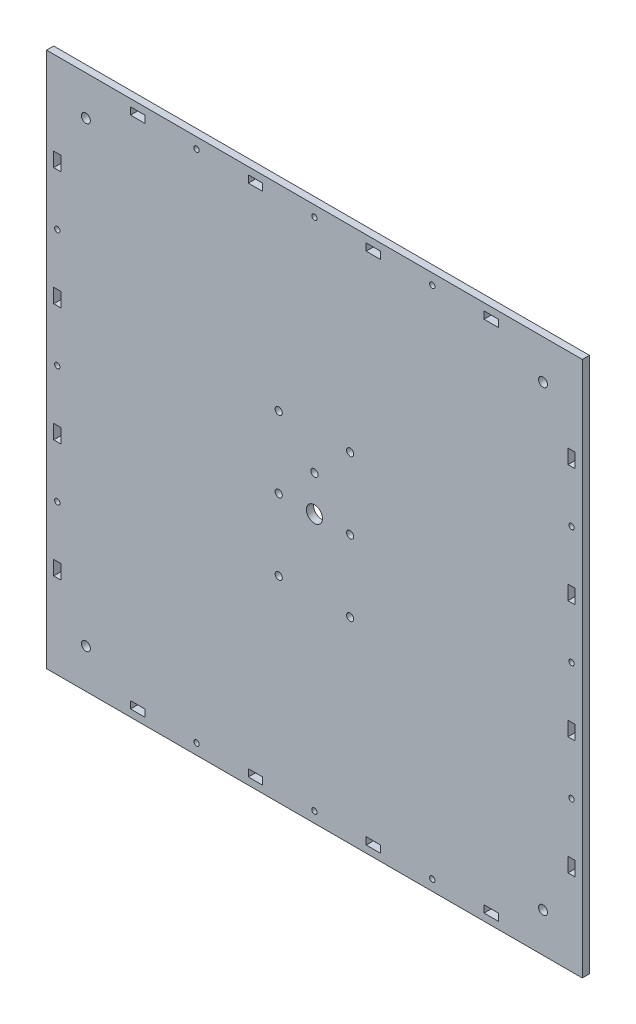
SolidWorks part; units mm, degrees
ref_plane "前视基准面" through (0, 0, 0) normal (0, 0, 1) x (1, 0, 0)
ref_plane "上视基准面" through (0, 0, 0) normal (0, 1, 0) x (1, 0, 0)
ref_plane "右视基准面" through (0, 0, 0) normal (1, 0, 0) x (0, 0, -1)
sketch "草图1" plane through (0, 0, 0) normal (0, 0, 1) x (1, 0, 0)
  line L0 (1.4571, -21.1871) -> (1.4571, -41.1871) construction
  line L1 (1.4571, -41.1871) -> (-18.5429, -41.1871) construction
  line L2 (1.4571, -21.1871) -> (1.4571, 44.8129) construction
  line L4 (151.4571, -41.1871) -> (151.4571, 108.8129)
  line L5 (151.4571, 108.8129) -> (-148.5429, 108.8129)
  line L6 (-148.5429, 108.8129) -> (-148.5429, -191.1871)
  line L7 (-148.5429, -191.1871) -> (151.4571, -191.1871)
  line L8 (151.4571, -191.1871) -> (151.4571, -41.1871)
  line L9 (-148.5429, -41.1871) -> (-161.9412, -41.1871) construction
  line L10 (1.4571, -191.1871) -> (1.4571, -181.0361) construction
  circle A0 centre (1.4571, -21.1871) radius 10 construction
  circle A1 centre (1.4571, -41.1871) radius 4.5
  circle A2 centre (-18.5429, -41.1871) radius 2
  circle A3 centre (-18.5429, -1.1871) radius 2
  circle A4 centre (21.4571, -1.1871) radius 2
  circle A5 centre (21.4571, -41.1871) radius 2
  circle A6 centre (1.4571, -21.1871) radius 241.4173 construction
  circle A7 centre (21.4571, -81.1871) radius 2
  circle A8 centre (-18.5429, -81.1871) radius 2
  dimension "D2" = 300
  dimension "D3" = 300
extrude "凸台-拉伸1" add sketch "草图1" along normal blind 4
sketch "草图2" plane through (0, 0, 4) normal (0, 0, 1) x (1, 0, 0)
  line L0 (-18.5429, -1.1871) -> (21.4571, -41.1871) construction
  circle A0 centre (1.4571, -21.1871) radius 2
extrude "切除-拉伸1" cut sketch "草图2" against normal blind 4 contours A0
sketch "草图3" plane through (0, 0, 4) normal (0, 0, 1) x (1, 0, 0)
  line L1 (96.4421, -183.1721) -> (104.4721, -183.1721)
  line L13 (1.4571, -191.1871) -> (1.4571, -185.1871) construction
  line L14 (-148.5429, -191.1871) -> (151.4571, -191.1871) construction
  line L15 (1.4571, -185.1871) -> (34.4571, -185.1871) construction
  line L16 (34.4571, -185.1871) -> (67.4571, -185.1871) construction
  line L17 (30.4421, -183.1721) -> (38.4721, -183.1721)
  line L18 (30.4421, -183.1721) -> (30.4421, -187.2021)
  line L19 (30.4421, -187.2021) -> (38.4721, -187.2021)
  line L20 (38.4721, -183.1721) -> (38.4721, -187.2021)
  line L21 (30.4421, -183.1721) -> (38.4721, -187.2021) construction
  line L22 (30.4421, -187.2021) -> (38.4721, -183.1721) construction
  line L23 (67.4571, -185.1871) -> (100.4571, -185.1871) construction
  line L24 (96.4421, -183.1721) -> (96.4421, -187.2021)
  line L25 (96.4421, -187.2021) -> (104.4721, -187.2021)
  line L26 (96.4421, -187.2021) -> (104.4721, -183.1721) construction
  line L27 (104.4721, -187.2021) -> (104.4721, -183.1721)
  line L28 (-35.5579, -183.1721) -> (-35.5579, -187.2021)
  line L29 (-27.5279, -183.1721) -> (-35.5579, -183.1721)
  line L30 (-27.5279, -183.1721) -> (-27.5279, -187.2021)
  line L31 (-27.5279, -187.2021) -> (-35.5579, -187.2021)
  line L32 (-93.5279, -183.1721) -> (-93.5279, -187.2021)
  line L33 (-101.5579, -187.2021) -> (-101.5579, -183.1721)
  line L34 (-93.5279, -183.1721) -> (-101.5579, -183.1721)
  line L35 (-93.5279, -187.2021) -> (-101.5579, -187.2021)
  line L36 (-140.5279, 53.7979) -> (-140.5279, 61.8279)
  line L37 (-144.5579, 53.7979) -> (-144.5579, 61.8279)
  line L38 (-144.5579, 61.8279) -> (-140.5279, 61.8279)
  line L39 (-140.5279, 53.7979) -> (-144.5579, 53.7979)
  line L40 (-140.5279, -12.2021) -> (-140.5279, -4.1721)
  line L41 (-140.5279, -4.1721) -> (-144.5579, -4.1721)
  line L42 (-144.5579, -12.2021) -> (-144.5579, -4.1721)
  line L43 (-140.5279, -12.2021) -> (-144.5579, -12.2021)
  line L44 (-140.5279, -70.1721) -> (-144.5579, -70.1721)
  line L45 (-140.5279, -70.1721) -> (-140.5279, -78.2021)
  line L46 (-144.5579, -70.1721) -> (-144.5579, -78.2021)
  line L47 (-140.5279, -78.2021) -> (-144.5579, -78.2021)
  line L48 (-140.5279, -136.1721) -> (-140.5279, -144.2021)
  line L49 (-144.5579, -136.1721) -> (-144.5579, -144.2021)
  line L50 (-140.5279, -136.1721) -> (-144.5579, -136.1721)
  line L51 (-144.5579, -144.2021) -> (-140.5279, -144.2021)
  line L52 (96.4421, 100.7979) -> (104.4721, 100.7979)
  line L53 (96.4421, 104.8279) -> (104.4721, 104.8279)
  line L54 (104.4721, 104.8279) -> (104.4721, 100.7979)
  line L55 (96.4421, 100.7979) -> (96.4421, 104.8279)
  line L56 (30.4421, 100.7979) -> (38.4721, 100.7979)
  line L57 (38.4721, 100.7979) -> (38.4721, 104.8279)
  line L58 (30.4421, 104.8279) -> (38.4721, 104.8279)
  line L59 (30.4421, 100.7979) -> (30.4421, 104.8279)
  line L60 (-27.5279, 100.7979) -> (-27.5279, 104.8279)
  line L61 (-27.5279, 100.7979) -> (-35.5579, 100.7979)
  line L62 (-27.5279, 104.8279) -> (-35.5579, 104.8279)
  line L63 (-35.5579, 100.7979) -> (-35.5579, 104.8279)
  line L64 (-93.5279, 100.7979) -> (-101.5579, 100.7979)
  line L65 (-93.5279, 104.8279) -> (-101.5579, 104.8279)
  line L66 (-93.5279, 100.7979) -> (-93.5279, 104.8279)
  line L67 (-101.5579, 104.8279) -> (-101.5579, 100.7979)
  line L68 (143.4421, -136.1721) -> (143.4421, -144.2021)
  line L69 (147.4721, -136.1721) -> (147.4721, -144.2021)
  line L70 (147.4721, -144.2021) -> (143.4421, -144.2021)
  line L71 (143.4421, -136.1721) -> (147.4721, -136.1721)
  line L72 (143.4421, -70.1721) -> (143.4421, -78.2021)
  line L73 (143.4421, -78.2021) -> (147.4721, -78.2021)
  line L74 (147.4721, -70.1721) -> (147.4721, -78.2021)
  line L75 (143.4421, -70.1721) -> (147.4721, -70.1721)
  line L76 (143.4421, -12.2021) -> (147.4721, -12.2021)
  line L77 (143.4421, -12.2021) -> (143.4421, -4.1721)
  line L78 (147.4721, -12.2021) -> (147.4721, -4.1721)
  line L79 (143.4421, -4.1721) -> (147.4721, -4.1721)
  line L80 (143.4421, 53.7979) -> (143.4421, 61.8279)
  line L81 (147.4721, 53.7979) -> (147.4721, 61.8279)
  line L82 (143.4421, 53.7979) -> (147.4721, 53.7979)
  line L83 (147.4721, 61.8279) -> (143.4421, 61.8279)
  circle A0 centre (1.4571, -185.1871) radius 1.5
  circle A1 centre (67.4571, -185.1871) radius 1.5
  circle A2 centre (-64.5429, -185.1871) radius 1.5
  circle A3 centre (-142.5429, 24.8129) radius 1.5
  circle A4 centre (-142.5429, -41.1871) radius 1.5
  circle A5 centre (-142.5429, -107.1871) radius 1.5
  circle A6 centre (67.4571, 102.8129) radius 1.5
  circle A7 centre (1.4571, 102.8129) radius 1.5
  circle A8 centre (-64.5429, 102.8129) radius 1.5
  circle A9 centre (145.4571, -107.1871) radius 1.5
  circle A10 centre (145.4571, -41.1871) radius 1.5
  circle A11 centre (145.4571, 24.8129) radius 1.5
  dimension "D1" = 8.03
  dimension "D3" = 4
  dimension "D2" = 4.03
extrude "切除-拉伸2" cut sketch "草图3" against normal blind 4
sketch "草图4" plane through (0, 0, 4) normal (0, 0, 1) x (1, 0, 0)
  line L2 (1.4571, 102.8129) -> (-142.5429, 102.8129) construction
  line L3 (-142.5429, 102.8129) -> (-38.5429, -1.1871) construction
  line L4 (1.4571, -1.1871) -> (-38.5429, -1.1871) construction
  line L5 (1.4571, 102.8129) -> (1.4571, -1.1871) construction
  line L6 (-9.5429, 88.8129) -> (-9.5429, 12.8129)
  line L7 (-12.5429, 9.8129) -> (-32.7439, 9.8129)
  line L8 (-110.8652, 86.6915) -> (-34.8652, 10.6915)
  line L9 (-12.5429, 91.8129) -> (-108.7439, 91.8129)
  line L10 (-9.5429, 91.8129) -> (-115.9865, 91.8129) construction
  line L11 (-115.9865, 91.8129) -> (-33.9865, 9.8129) construction
  line L12 (-9.5429, 91.8129) -> (-9.5429, 9.8129) construction
  line L13 (-9.5429, 9.8129) -> (-33.9865, 9.8129) construction
  line L14 (12.4571, 88.8129) -> (12.4571, 12.8129)
  line L15 (15.4571, 9.8129) -> (35.6582, 9.8129)
  line L16 (113.7795, 86.6915) -> (37.7795, 10.6915)
  line L17 (15.4571, 91.8129) -> (111.6582, 91.8129)
  line L18 (1.4571, -41.1871) -> (42.8173, -41.1871) construction
  line L19 (-12.5429, -174.1871) -> (-108.7439, -174.1871)
  line L20 (-110.8652, -169.0658) -> (-34.8652, -93.0658)
  line L21 (-12.5429, -92.1871) -> (-32.7439, -92.1871)
  line L22 (-9.5429, -171.1871) -> (-9.5429, -95.1871)
  line L23 (-49.5429, -27.1871) -> (-49.5429, -6.9861)
  line L24 (15.4571, -174.1871) -> (111.6582, -174.1871)
  line L25 (113.7795, -169.0658) -> (37.7795, -93.0658)
  line L26 (15.4571, -92.1871) -> (35.6582, -92.1871)
  line L27 (12.4571, -171.1871) -> (12.4571, -95.1871)
  line L28 (-128.5429, -30.1871) -> (-52.5429, -30.1871)
  line L29 (-131.5429, -27.1871) -> (-131.5429, 69.0139)
  line L30 (-126.4215, 71.1352) -> (-50.4215, -4.8648)
  line L31 (129.3358, 71.1352) -> (53.3358, -4.8648)
  line L32 (134.4571, -27.1871) -> (134.4571, 69.0139)
  line L33 (131.4571, -30.1871) -> (55.4571, -30.1871)
  line L34 (52.4571, -27.1871) -> (52.4571, -6.9861)
  line L35 (52.4571, -55.1871) -> (52.4571, -75.3882)
  line L36 (131.4571, -52.1871) -> (55.4571, -52.1871)
  line L37 (134.4571, -55.1871) -> (134.4571, -151.3882)
  line L38 (129.3358, -153.5095) -> (53.3358, -77.5095)
  line L39 (-126.4215, -153.5095) -> (-50.4215, -77.5095)
  line L40 (-131.5429, -55.1871) -> (-131.5429, -151.3882)
  line L41 (-128.5429, -52.1871) -> (-52.5429, -52.1871)
  line L42 (-49.5429, -55.1871) -> (-49.5429, -75.3882)
  arc A0 (-108.7439, 91.8129) -> (-110.8652, 86.6915) centre (-108.7439, 88.8129) ccw
  arc A1 (-9.5429, 12.8129) -> (-12.5429, 9.8129) centre (-12.5429, 12.8129) cw
  arc A2 (-32.7439, 9.8129) -> (-34.8652, 10.6915) centre (-32.7439, 12.8129) cw
  arc A3 (-9.5429, 88.8129) -> (-12.5429, 91.8129) centre (-12.5429, 88.8129) ccw
  arc A4 (111.6582, 91.8129) -> (113.7795, 86.6915) centre (111.6582, 88.8129) cw
  arc A5 (12.4571, 88.8129) -> (15.4571, 91.8129) centre (15.4571, 88.8129) cw
  arc A6 (12.4571, 12.8129) -> (15.4571, 9.8129) centre (15.4571, 12.8129) ccw
  arc A7 (35.6582, 9.8129) -> (37.7795, 10.6915) centre (35.6582, 12.8129) ccw
  arc A8 (-9.5429, -171.1871) -> (-12.5429, -174.1871) centre (-12.5429, -171.1871) cw
  arc A9 (-32.7439, -92.1871) -> (-34.8652, -93.0658) centre (-32.7439, -95.1871) ccw
  arc A10 (-9.5429, -95.1871) -> (-12.5429, -92.1871) centre (-12.5429, -95.1871) ccw
  arc A11 (-108.7439, -174.1871) -> (-110.8652, -169.0658) centre (-108.7439, -171.1871) cw
  arc A12 (35.6582, -92.1871) -> (37.7795, -93.0658) centre (35.6582, -95.1871) cw
  arc A13 (12.4571, -95.1871) -> (15.4571, -92.1871) centre (15.4571, -95.1871) cw
  arc A14 (12.4571, -171.1871) -> (15.4571, -174.1871) centre (15.4571, -171.1871) ccw
  arc A15 (111.6582, -174.1871) -> (113.7795, -169.0658) centre (111.6582, -171.1871) ccw
  arc A16 (-128.5429, -30.1871) -> (-131.5429, -27.1871) centre (-128.5429, -27.1871) cw
  arc A17 (-131.5429, 69.0139) -> (-126.4215, 71.1352) centre (-128.5429, 69.0139) cw
  arc A18 (-49.5429, -6.9861) -> (-50.4215, -4.8648) centre (-52.5429, -6.9861) ccw
  arc A19 (-52.5429, -30.1871) -> (-49.5429, -27.1871) centre (-52.5429, -27.1871) ccw
  arc A20 (55.4571, -30.1871) -> (52.4571, -27.1871) centre (55.4571, -27.1871) cw
  arc A21 (52.4571, -6.9861) -> (53.3358, -4.8648) centre (55.4571, -6.9861) cw
  arc A22 (134.4571, 69.0139) -> (129.3358, 71.1352) centre (131.4571, 69.0139) ccw
  arc A23 (131.4571, -30.1871) -> (134.4571, -27.1871) centre (131.4571, -27.1871) ccw
  arc A24 (131.4571, -52.1871) -> (134.4571, -55.1871) centre (131.4571, -55.1871) cw
  arc A25 (134.4571, -151.3882) -> (129.3358, -153.5095) centre (131.4571, -151.3882) cw
  arc A26 (52.4571, -75.3882) -> (53.3358, -77.5095) centre (55.4571, -75.3882) ccw
  arc A27 (55.4571, -52.1871) -> (52.4571, -55.1871) centre (55.4571, -55.1871) ccw
  arc A28 (-52.5429, -52.1871) -> (-49.5429, -55.1871) centre (-52.5429, -55.1871) cw
  arc A29 (-49.5429, -75.3882) -> (-50.4215, -77.5095) centre (-52.5429, -75.3882) cw
  arc A30 (-131.5429, -151.3882) -> (-126.4215, -153.5095) centre (-128.5429, -151.3882) ccw
  arc A31 (-128.5429, -52.1871) -> (-131.5429, -55.1871) centre (-128.5429, -55.1871) ccw
  dimension "D2" = 3
  dimension "D3" = 3
  dimension "D1" = 11
sketch "草图5" plane through (0, 0, 4) normal (0, 0, 1) x (1, 0, 0)
  line L0 (1.4571, -41.1871) -> (-148.5429, 108.8129) construction
  line L1 (-126.5429, 86.8129) -> (-126.5429, 108.8129) construction
  line L2 (151.4571, 108.8129) -> (-148.5429, 108.8129) construction
  circle A0 centre (-126.5429, 86.8129) radius 2.5
  circle A1 centre (129.4571, 86.8129) radius 2.5
  circle A2 centre (129.4571, -169.1871) radius 2.5
  circle A3 centre (-126.5429, -169.1871) radius 2.5
  dimension "D1" = 4
extrude "切除-拉伸4" cut sketch "草图5" against normal blind 10
